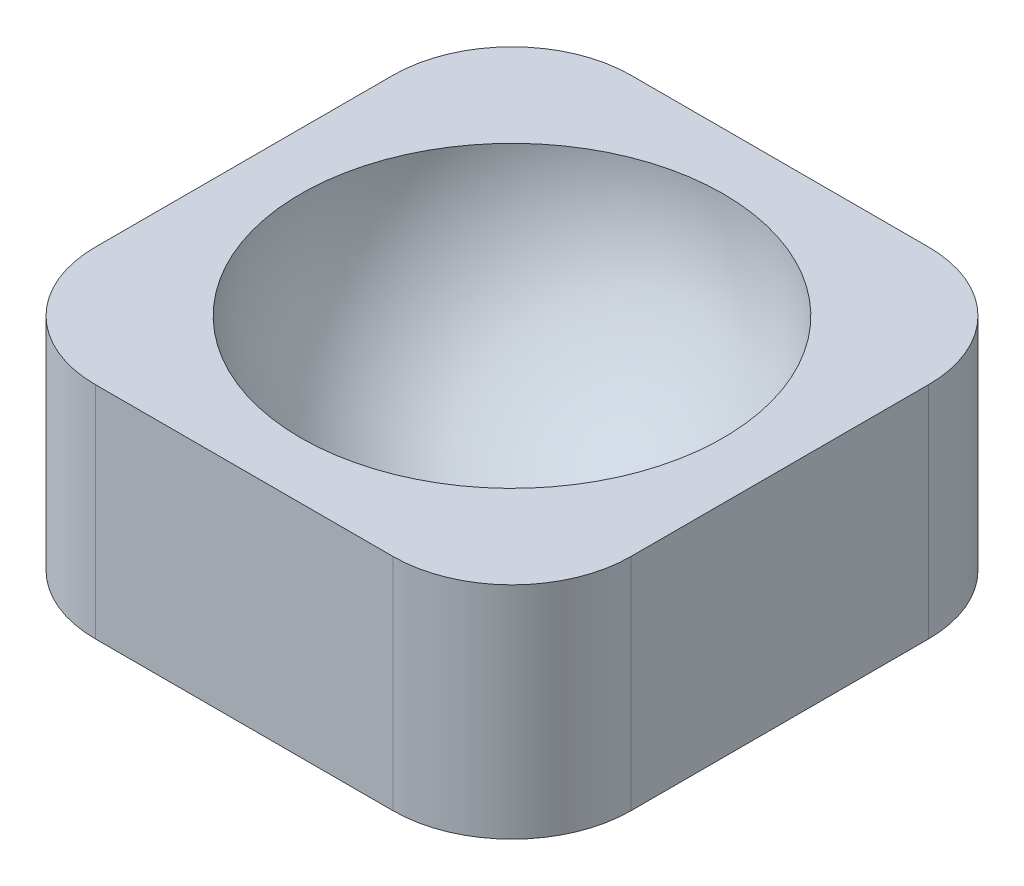
SolidWorks part; units mm, degrees
material "AISI 4340 Steel, normalized"
ref_plane "Front Plane" through (0, 0, 0) normal (0, 0, 1) x (1, 0, 0)
ref_plane "Top Plane" through (0, 0, 0) normal (0, 1, 0) x (1, 0, 0)
ref_plane "Right Plane" through (0, 0, 0) normal (1, 0, 0) x (0, 0, -1)
sketch "Sketch1" plane through (0, 0, 0) normal (0, 1, 0) x (1, 0, 0)
  line L1 (0, 0) -> (-114.3, 0)
  line L2 (0, 0) -> (0, 114.3)
  line L3 (0, 114.3) -> (-114.3, 114.3)
  line L4 (-114.3, 0) -> (-114.3, 114.3)
  circle A0 centre (-57.15, 57.15) radius 44.45
  point P7 (-101.6, 57.15)
  point P8 (-114.3, 57.15)
  point P9 (0, 57.15)
  point P10 (-57.15, 114.3)
  point P11 (-57.15, 0)
  point P13 (-57.15, 101.6)
  dimension "D1" = 88.9
  dimension "D2" = 12.7
  dimension "D3" = 12.7
extrude "Boss-Extrude1" add sketch "Sketch1" along normal blind 46.99 contours L4 L1 L2 L3 A0 | A0
sketch "Sketch2" plane through (0, 46.99, 0) normal (0, 1, 0) x (1, 0, 0)
  line L0 (-57.15, 114.3) -> (-57.15, 0) construction
  line L1 (0, 114.3) -> (-114.3, 114.3) construction
  line L2 (0, 0) -> (-114.3, 0) construction
  line L3 (-57.15, 102.235) -> (-57.15, 12.065)
  circle A0 centre (-57.15, 57.15) radius 45.085
  point P10 (-57.15, 12.954)
  dimension "D1" = 90.17
revolve "Cut-Revolve1" cut sketch "Sketch2" angle 180 about L0
fillet "Fillet1" radius 25.4 4 edges at (0, 23.495, 0) (-114.3, 23.495, 0) (-114.3, 23.495, -114.3) (0, 23.495, -114.3)
sketch "Sketch3" plane through (0, 0, 0) normal (0, -1, 0) x (1, 0, 0)
  line L0 (-57.15, -114.3) -> (-57.15, 0) construction
  line L1 (-25.4, -114.3) -> (-88.9, -114.3) construction
  line L2 (-25.4, 0) -> (-88.9, 0) construction
  line L3 (0, -57.15) -> (-114.3, -57.15) construction
  line L4 (0, -25.4) -> (0, -88.9) construction
  line L5 (-114.3, -25.4) -> (-114.3, -88.9) construction
equation "\"D3@Sketch1\"=\"D2@Sketch1\""
